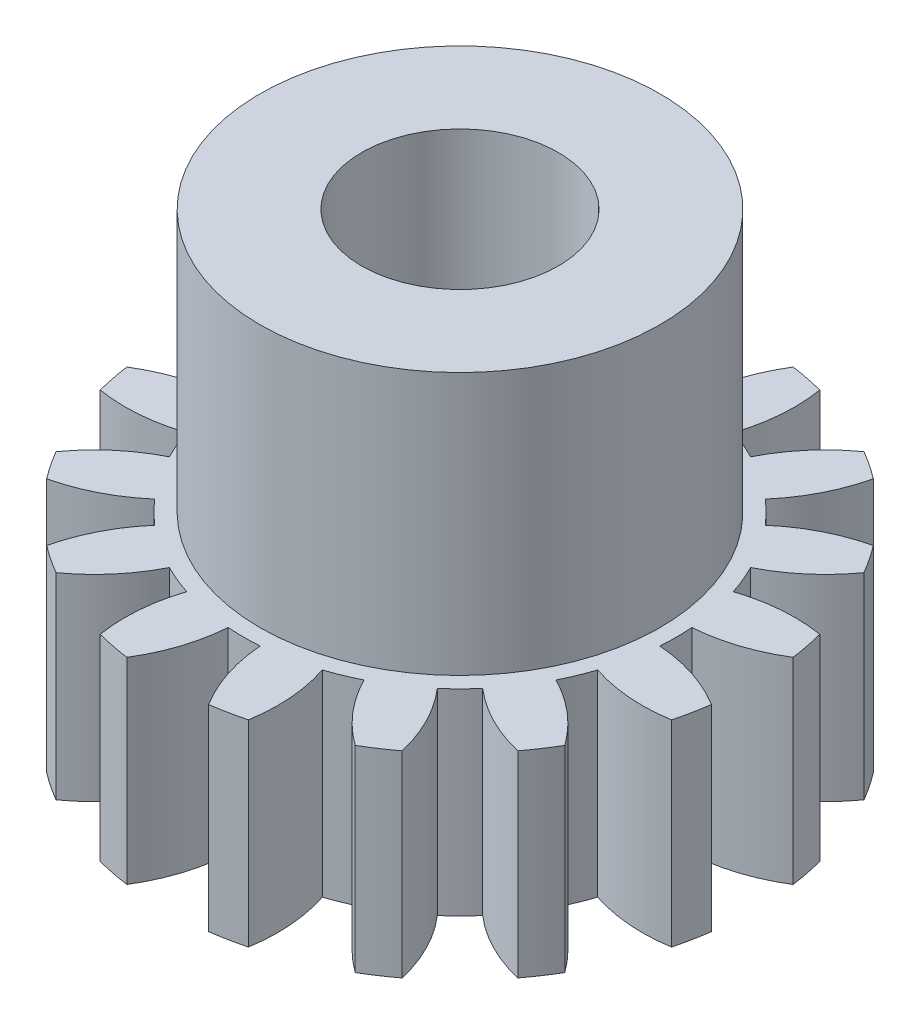
SolidWorks part; units mm, degrees
ref_plane "Front Plane" through (0, 0, 0) normal (0, 0, 1) x (1, 0, 0)
ref_plane "Top Plane" through (0, 0, 0) normal (0, 1, 0) x (1, 0, 0)
ref_plane "Right Plane" through (0, 0, 0) normal (1, 0, 0) x (0, 0, -1)
sketch "Sketch1" plane through (0, 0, 0) normal (0, 1, 0) x (1, 0, 0)
  circle A0 centre (0, 0) radius 4
  circle A1 centre (0, 0) radius 4.5
  circle A2 centre (0, 0) radius 3.3
  dimension "D1" = 8
  dimension "D2" = 9
  dimension "D3" = 1.2
extrude "Boss-Extrude1" add sketch "Sketch1" along normal mid plane 3 contours A1 A0 | A0 A2 | A2
sketch "Sketch3" plane through (0, 0, 0) normal (0, 1, 0) x (1, 0, 0)
  line L0 (0, 0) -> (0, 4.5) construction
  line L1 (-0.3921, 3.9807) -> (0.3921, 3.9807) construction
  line L2 (-0.2439, 3.291) -> (0, 0) construction
  line L3 (0, 2.9035) -> (-1.0108, 5.6808) construction
  line L4 (0, 0) -> (0.8779, 4.4135) construction
  line L5 (0.3921, 3.9807) -> (1.1611, 3.8278) construction
  circle A0 centre (0, 0) radius 4.5 construction
  arc A1 (-1.8198, 5.4755) -> (-0.2439, 3.291) centre (-2.8097, 3.1008) cw
  arc A2 (1.8198, 5.4755) -> (0.2439, 3.291) centre (2.8097, 3.1008) ccw
  circle A3 centre (0, 0) radius 3.3 construction
  arc A4 (0.2439, 3.291) -> (-0.2439, 3.291) centre (0, 0) ccw
  circle A5 centre (0, 0) radius 4 construction
  circle A6 centre (0, 0) radius 4.5 construction
  circle A7 centre (0, 0) radius 5.77
  arc A8 (1.8198, 5.4755) -> (-1.8198, 5.4755) centre (0, 0) ccw
  dimension "D2" = 20
  dimension "D3" = 11.25
  dimension "D1" = 1.27
extrude "Cut-Extrude1" cut sketch "Sketch3" against normal through all both and the other way through all
fillet "Fillet2" [suppressed] radius 0.15
pattern_circular "CirPattern1" count 16 over 360 about axis through (0, 0, 0) along (0, 1, 0) of "Cut-Extrude1", "Fillet2"
sketch "Sketch4" plane through (0, 0, 0) normal (0, 1, 0) x (1, 0, 0)
  circle A0 centre (0, 0) radius 1.5
  dimension "D1" = 3
extrude "Cut-Extrude2" cut sketch "Sketch4" along normal through all both and the other way through all
sketch "Sketch5" plane through (0, 1.5, 0) normal (0, 1, 0) x (1, 0, 0)
  circle A0 centre (0, 0) radius 1.5
  circle A1 centre (0, 0) radius 3.05
  circle A2 centre (0, 0) radius 1.5 construction
  arc A3 (2.4996, 2.1546) -> (2.1546, 2.4996) centre (0, 0) ccw construction
  dimension "D1" = 0.25
extrude "Boss-Extrude2" add sketch "Sketch5" along normal blind 4
equation "\"Module\"= .5"
equation "\"Number of Teeth\"= 16"
equation "\"D1@Sketch1\"=\"Module\"* \"Number of Teeth\""
equation "\"D2@Sketch1\"=(\"Number of Teeth\" + 2) * \"Module\""
equation "\"D3@Sketch1\"=\"Module\" * if( \"Module\" => 1.25, 2.25, 2.4)"
equation "\"D3@Sketch3\"=180 / \"Number of Teeth\""
equation "\"D1@Fillet2\"=.3 * \"Module\""
equation "\"D1@CirPattern1\"=\"Number of Teeth\""
